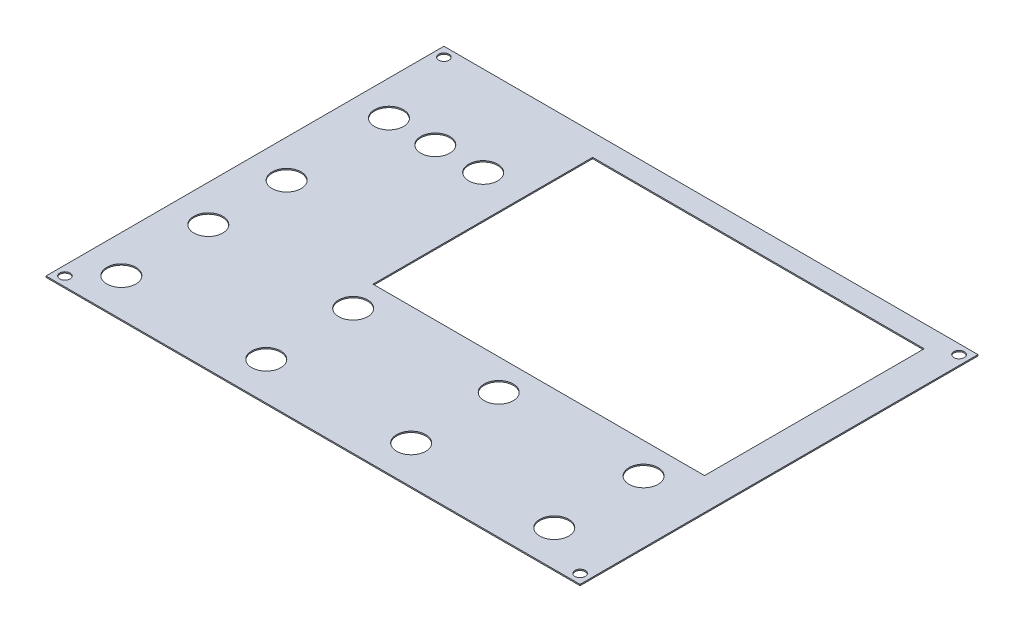
SolidWorks part; units mm, degrees
ref_plane "Front Plane" through (0, 0, 0) normal (0, 0, 1) x (1, 0, 0)
ref_plane "Top Plane" through (0, 0, 0) normal (0, 1, 0) x (1, 0, 0)
ref_plane "Right Plane" through (0, 0, 0) normal (1, 0, 0) x (0, 0, -1)
sketch "Sketch1" plane through (0, 0, 0) normal (0, 1, 0) x (1, 0, 0)
  line L0 (71.763, 1.431) -> (81.563, 1.431) construction
  line L1 (0, 0) -> (124.3, 0) construction
  line L2 (0, 0) -> (0, 91.44) construction
  line L3 (0, 91.44) -> (124.3, 91.44) construction
  line L4 (124.3, 0) -> (124.3, 91.44) construction
  line L5 (-2.286, -2.286) -> (126.586, -2.286)
  line L6 (-2.286, -2.286) -> (-2.286, 93.726)
  line L7 (-2.286, 93.726) -> (126.586, 93.726)
  line L8 (126.586, -2.286) -> (126.586, 93.726)
  line L9 (1.831, 1.431) -> (11.631, 1.431) construction
  line L10 (1.831, 1.431) -> (1.831, 12.331) construction
  line L11 (1.831, 12.331) -> (11.631, 12.331) construction
  line L12 (11.631, 1.431) -> (11.631, 12.331) construction
  line L13 (36.797, 1.431) -> (46.597, 1.431) construction
  line L14 (36.797, 1.431) -> (36.797, 12.331) construction
  line L15 (36.797, 12.331) -> (46.597, 12.331) construction
  line L16 (46.597, 1.431) -> (46.597, 12.331) construction
  line L17 (71.763, 1.431) -> (71.763, 12.331) construction
  line L18 (71.763, 12.331) -> (81.563, 12.331) construction
  line L19 (81.563, 1.431) -> (81.563, 12.331) construction
  line L20 (106.73, 0.99) -> (116.53, 0.99) construction
  line L21 (106.73, 0.99) -> (106.73, 11.89) construction
  line L22 (106.73, 11.89) -> (116.53, 11.89) construction
  line L23 (116.53, 0.99) -> (116.53, 11.89) construction
  line L24 (71.645, 22.273) -> (81.645, 22.273) construction
  line L25 (106.601, 22.273) -> (116.601, 22.273) construction
  line L26 (106.601, 22.273) -> (106.601, 33.773) construction
  line L27 (106.601, 33.773) -> (116.601, 33.773) construction
  line L28 (116.601, 22.273) -> (116.601, 33.773) construction
  line L29 (71.645, 22.273) -> (71.645, 33.773) construction
  line L30 (71.645, 33.773) -> (81.645, 33.773) construction
  line L31 (81.645, 22.273) -> (81.645, 33.773) construction
  line L32 (36.524, 22.273) -> (46.524, 22.273) construction
  line L33 (36.524, 22.273) -> (36.524, 33.773) construction
  line L34 (36.524, 33.773) -> (46.524, 33.773) construction
  line L35 (46.524, 22.273) -> (46.524, 33.773) construction
  line L36 (1.568, 22.273) -> (11.568, 22.273) construction
  line L37 (1.568, 22.273) -> (1.568, 33.773) construction
  line L38 (1.568, 33.773) -> (11.568, 33.773) construction
  line L39 (11.568, 22.273) -> (11.568, 33.773) construction
  line L40 (1.73, 41.004) -> (11.73, 41.004) construction
  line L41 (1.73, 41.004) -> (1.73, 52.504) construction
  line L42 (1.73, 52.504) -> (11.73, 52.504) construction
  line L43 (11.73, 41.004) -> (11.73, 52.504) construction
  line L44 (13.842, 78.44) -> (20.702, 78.44) construction
  line L45 (2.666, 78.44) -> (9.526, 78.44) construction
  line L46 (2.666, 78.44) -> (2.666, 65.74) construction
  line L47 (2.666, 65.74) -> (9.526, 65.74) construction
  line L48 (9.526, 78.44) -> (9.526, 65.74) construction
  line L49 (13.842, 78.44) -> (13.842, 65.74) construction
  line L50 (13.842, 65.74) -> (20.702, 65.74) construction
  line L51 (20.702, 78.44) -> (20.702, 65.74) construction
  line L52 (25.4, 78.44) -> (32.26, 78.44) construction
  line L53 (25.4, 78.44) -> (25.4, 65.74) construction
  line L54 (25.4, 65.74) -> (32.26, 65.74) construction
  line L55 (32.26, 78.44) -> (32.26, 65.74) construction
  line L56 (6.731, 12.331) -> (6.731, 1.431) construction
  line L57 (41.697, 12.331) -> (41.697, 1.431) construction
  line L58 (76.663, 12.331) -> (76.663, 1.431) construction
  line L59 (111.63, 11.89) -> (111.63, 0.99) construction
  line L60 (111.601, 33.773) -> (111.601, 22.273) construction
  line L61 (76.645, 33.773) -> (76.645, 22.273) construction
  line L62 (41.524, 33.773) -> (41.524, 22.273) construction
  line L63 (6.568, 33.773) -> (6.568, 22.273) construction
  line L64 (6.73, 52.504) -> (6.73, 41.004) construction
  line L65 (6.096, 78.44) -> (6.096, 65.74) construction
  line L66 (17.272, 78.44) -> (17.272, 65.74) construction
  line L67 (28.83, 78.44) -> (28.83, 65.74) construction
  line L69 (38.8754, 88.452) -> (118.8754, 88.452)
  line L70 (38.8754, 88.452) -> (38.8754, 35.452)
  line L71 (38.8754, 35.452) -> (118.8754, 35.452)
  line L72 (118.8754, 88.452) -> (118.8754, 35.452)
  circle A0 centre (0, 91.44) radius 1.25
  circle A1 centre (124.3, 91.44) radius 1.25
  circle A2 centre (0, 0) radius 1.25
  circle A3 centre (124.3, 0) radius 1.25
  circle A4 centre (6.731, 6.881) radius 3.5
  circle A5 centre (41.697, 6.881) radius 3.5
  circle A6 centre (76.663, 6.881) radius 3.5
  circle A7 centre (111.63, 6.44) radius 3.5
  circle A8 centre (6.73, 46.754) radius 3.5
  circle A9 centre (6.568, 28.023) radius 3.5
  circle A10 centre (41.524, 28.023) radius 3.5
  circle A11 centre (76.645, 28.023) radius 3.5
  circle A12 centre (111.601, 28.023) radius 3.5
  circle A13 centre (6.096, 72.09) radius 3.5
  circle A14 centre (17.272, 72.09) radius 3.5
  circle A15 centre (28.83, 72.09) radius 3.5
  dimension "D3" = 2.5
  dimension "D4" = 2.5
  dimension "D5" = 2.5
  dimension "D6" = 2.5
  dimension "D7" = 2.286
  dimension "D8" = 2.286
  dimension "D9" = 2.286
  dimension "D10" = 2.286
  dimension "D54" = 7
  dimension "D55" = 7
  dimension "D56" = 7
  dimension "D57" = 7
  dimension "D58" = 7
  dimension "D59" = 7
  dimension "D60" = 7
  dimension "D61" = 7
  dimension "D62" = 7
  dimension "D63" = 7
  dimension "D64" = 7
  dimension "D65" = 7
  dimension "D1" = 124.3
  dimension "D2" = 91.44
  dimension "D11" = 9.8
  dimension "D12" = 10.9
  dimension "D13" = 1.831
  dimension "D14" = 1.431
  dimension "D15" = 9.8
  dimension "D16" = 10.9
  dimension "D17" = 25.166
  dimension "D18" = 1.431
  dimension "D19" = 9.8
  dimension "D20" = 10.9
  dimension "D21" = 1.431
  dimension "D22" = 25.166
  dimension "D23" = 9.8
  dimension "D24" = 10.9
  dimension "D25" = 25.167
  dimension "D26" = 0.99
  dimension "D27" = 10
  dimension "D28" = 11.5
  dimension "D29" = 7.699
  dimension "D30" = 22.273
  dimension "D31" = 10
  dimension "D32" = 11.5
  dimension "D33" = 24.956
  dimension "D34" = 10
  dimension "D35" = 11.5
  dimension "D36" = 25.121
  dimension "D37" = 10
  dimension "D38" = 11.5
  dimension "D39" = 24.956
  dimension "D40" = 10
  dimension "D41" = 11.5
  dimension "D42" = 38.936
  dimension "D43" = 1.73
  dimension "D44" = 6.86
  dimension "D45" = 12.7
  dimension "D46" = 2.666
  dimension "D47" = 13
  dimension "D48" = 12.7
  dimension "D49" = 6.86
  dimension "D50" = 13.842
  dimension "D51" = 6.86
  dimension "D52" = 12.7
  dimension "D53" = 25.4
  dimension "D66" = 53
  dimension "D67" = 80
  dimension "D68" = 5.274
  dimension "D69" = 7.7106
extrude "Boss-Extrude1" add sketch "Sketch1" along normal blind 0.3
